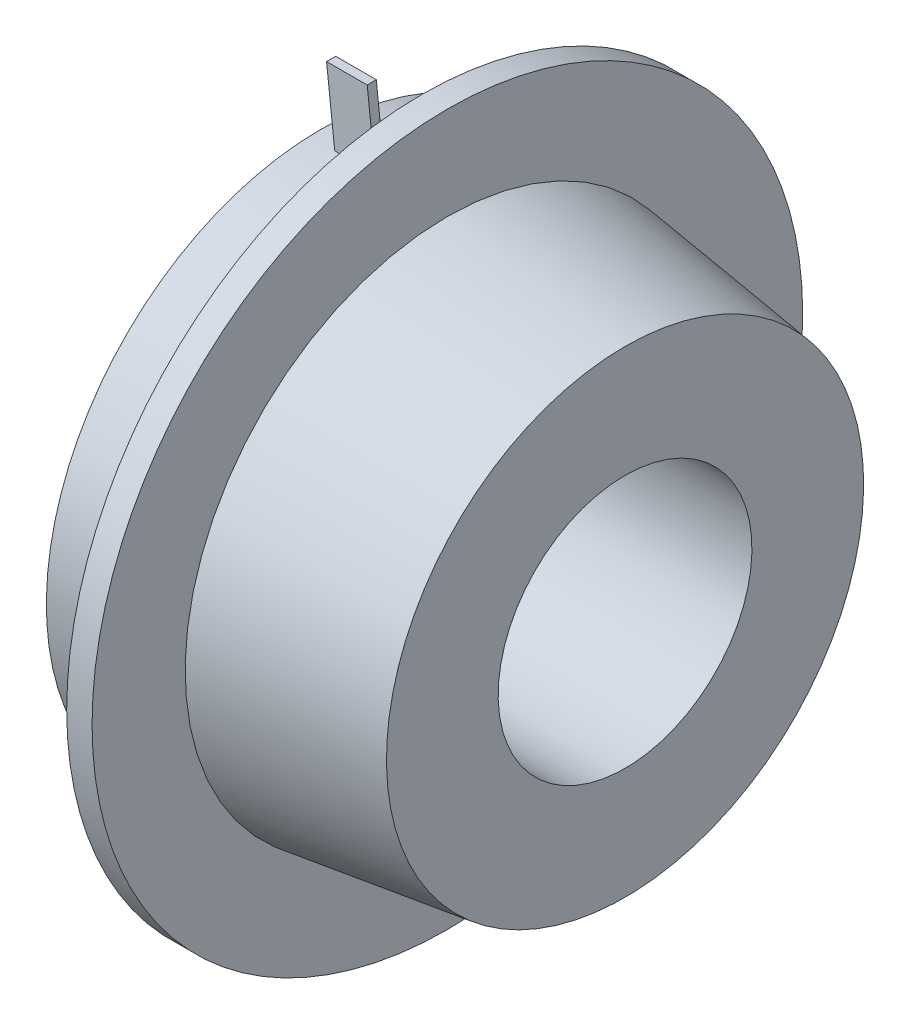
SolidWorks part; units mm, degrees
ref_plane "Front Plane" through (0, 0, 0) normal (0, 0, 1) x (1, 0, 0)
ref_plane "Top Plane" through (0, 0, 0) normal (0, 1, 0) x (1, 0, 0)
ref_plane "Right Plane" through (0, 0, 0) normal (1, 0, 0) x (0, 0, -1)
sketch "Sketch1" plane through (0, 0, 0) normal (0, 0, 1) x (1, 0, 0)
  line L0 (0, 0) -> (3000, 0) construction
  line L1 (1250, 250) -> (1250, 540)
  line L2 (1250, 540) -> (1400, 530)
  line L3 (1400, 530) -> (1550, 510)
  line L4 (1550, 510) -> (1700, 490)
  line L5 (1700, 490) -> (1850, 470)
  line L6 (1850, 470) -> (1850, 250)
  line L7 (1850, 250) -> (1250, 250)
revolve "Revolve1" add sketch "Sketch1" angle 360 about L0
sketch "Sketch2" plane through (0, 0, 0) normal (0, 0, 1) x (1, 0, 0)
  line L0 (1300, 500) -> (1280, 680)
  line L1 (1280, 680) -> (1360, 680)
  line L2 (1360, 680) -> (1380, 500)
  line L3 (1380, 500) -> (1300, 500)
extrude "Boss-Extrude1" add sketch "Sketch2" along normal blind 18 separate body
sketch "Sketch3" plane through (0, 0, 0) normal (0, 0, 1) x (1, 0, 0)
  line L0 (0, 0) -> (3000, 0) construction
  line L1 (1450, 500) -> (1450, 700)
  line L2 (1450, 700) -> (1500, 700)
  line L3 (1500, 700) -> (1500, 500)
  line L4 (1500, 500) -> (1450, 500)
revolve "Revolve2" add sketch "Sketch3" angle 360 about L0
